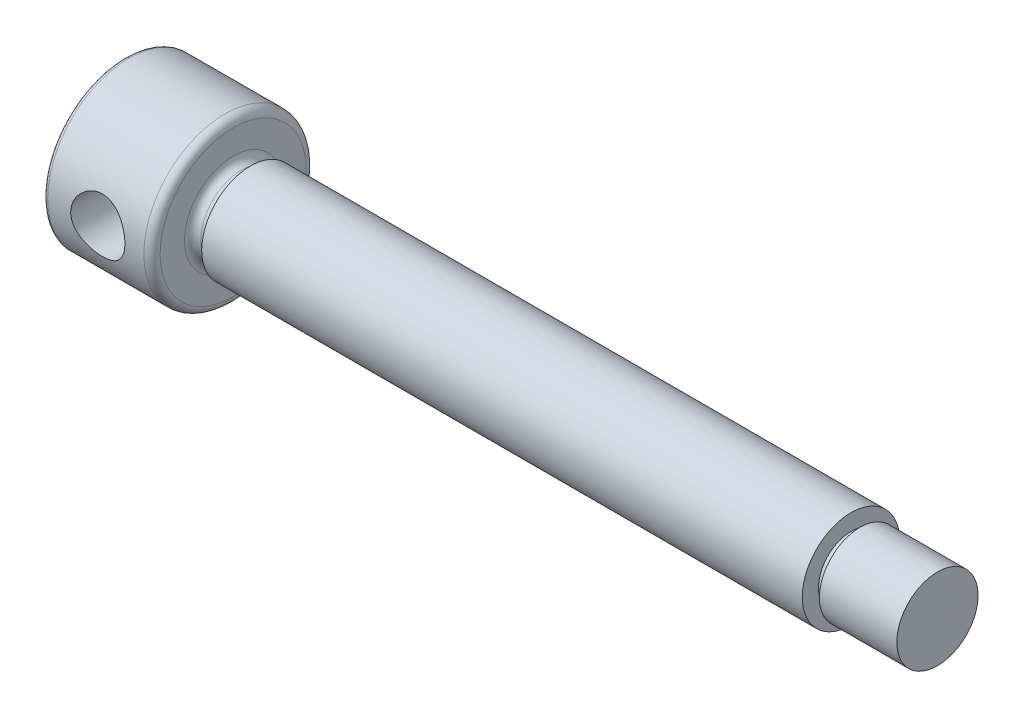
SolidWorks part; units mm, degrees
ref_plane "Front Plane" through (0, 0, 0) normal (0, 0, 1) x (1, 0, 0)
ref_plane "Top Plane" through (0, 0, 0) normal (0, 1, 0) x (1, 0, 0)
ref_plane "Right Plane" through (0, 0, 0) normal (1, 0, 0) x (0, 0, -1)
sketch "Sketch1" plane through (0, 0, 0) normal (0, 0, 1) x (1, 0, 0)
  line L0 (0, 0) -> (300, 0)
  line L1 (300, 0) -> (300, 15)
  line L2 (300, 15) -> (271.4199, 15)
  line L3 (271.4199, 15) -> (271.4199, 12)
  line L4 (271.4199, 12) -> (268.0899, 12)
  line L5 (268.0899, 12) -> (268.0899, 18)
  line L6 (268.0899, 18) -> (46.35, 18)
  line L7 (46.35, 18) -> (46.35, 15)
  line L8 (46.35, 15) -> (40, 15)
  line L9 (40, 15) -> (40, 30)
  line L10 (40, 30) -> (0, 30)
  line L11 (0, 30) -> (0, 0)
  point P9 (40, 7.5982)
  point P14 (230.7679, 6.6328)
  point P15 (210.4954, 3.415)
  point P16 (271.4199, 15)
  dimension "D1" = 300
  dimension "D2" = 30
  dimension "D3" = 40
  dimension "D4" = 3
  dimension "D5" = 6.35
  dimension "D6" = 3.33
  dimension "D7" = 15
  dimension "D8" = 15
  dimension "D9" = 6
revolve "Revolve1" add sketch "Sketch1" angle 360 about L0
fillet "Fillet1" radius 1.5 1 edges at (0, 0, 30)
sketch "Sketch3" plane through (0, 0, 0) normal (0, 0, 1) x (1, 0, 0)
  line L0 (0, 0) -> (40, 0) construction
  line L1 (40, -15) -> (40, 15) construction
  circle A0 centre (20, 0) radius 10
  dimension "D1" = 20
extrude "Cut-Extrude1" cut sketch "Sketch3" against normal mid plane 273
fillet "Fillet2" radius 3 1 edges at (40, 0, 15)
fillet "Fillet3" radius 3 1 edges at (40, 0, 30)
